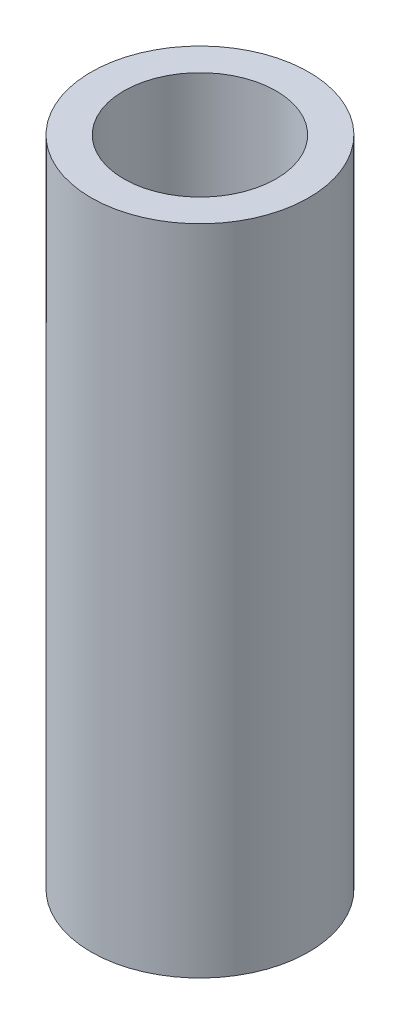
SolidWorks part; units mm, degrees
material "ABS"
ref_plane "Front Plane" through (0, 0, 0) normal (0, 0, 1) x (1, 0, 0)
ref_plane "Top Plane" through (0, 0, 0) normal (0, 1, 0) x (1, 0, 0)
ref_plane "Right Plane" through (0, 0, 0) normal (1, 0, 0) x (0, 0, -1)
sketch "Sketch1" plane through (0, 0, 0) normal (0, 1, 0) x (1, 0, 0)
  circle A0 centre (0, 0) radius 2.5
  circle A1 centre (0, 0) radius 1.75
  dimension "D1" = 5
  dimension "D2" = 3.5
extrude "Boss-Extrude1" add sketch "Sketch1" along normal blind 15
